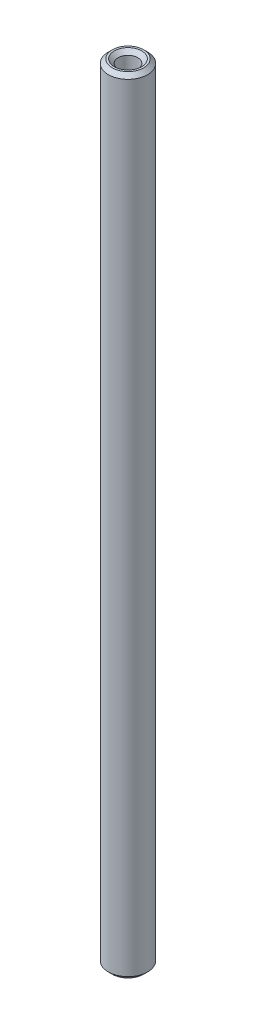
SolidWorks part; units mm, degrees
material "6061-T6 (SS)"
ref_plane "前视基准面" through (0, 0, 0) normal (0, 0, 1) x (1, 0, 0)
ref_plane "上视基准面" through (0, 0, 0) normal (0, 1, 0) x (1, 0, 0)
ref_plane "右视基准面" through (0, 0, 0) normal (1, 0, 0) x (0, 0, -1)
sketch "Sketch1" plane through (0, 0, 0) normal (0, 1, 0) x (1, 0, 0)
  circle A0 centre (0, 0) radius 2.5
  circle A1 centre (0, 0) radius 1.25
  dimension "D1" = 5
  dimension "D2" = 2.5
extrude "Extrude1" add sketch "Sketch1" along normal mid plane 100
cosmetic thread "Cosmetic Thread1" parameters "D1"=4, "D2"=3
cosmetic thread "Cosmetic Thread2" parameters "D1"=4, "D2"=3
chamfer "Chamfer1" distance 0.5 angle 45 4 edges at (0, -50, 1.25) (0, -50, 2.5) (0, 50, 1.25) (0, 50, 2.5)
other "冻结***"
